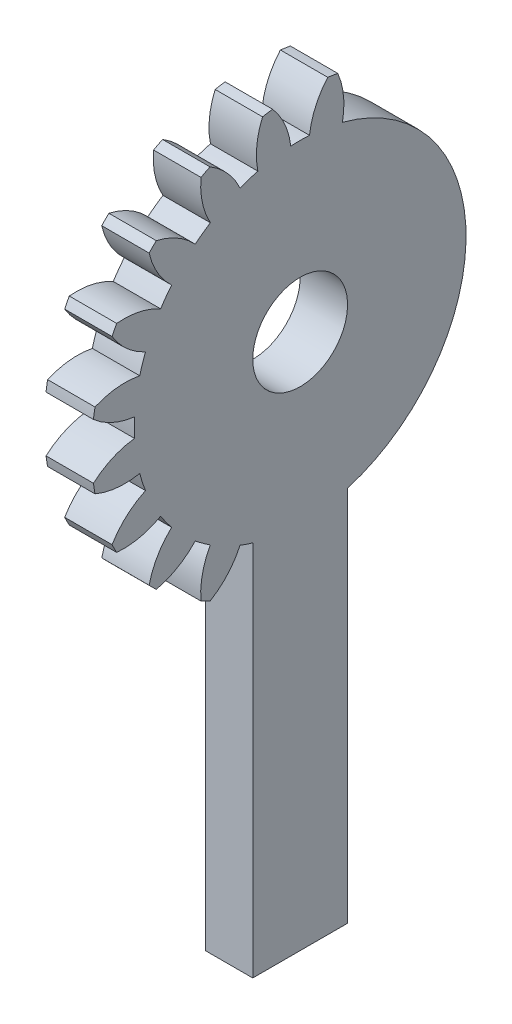
SolidWorks part; units mm, degrees
ref_plane "Plane1" through (0, 0, 0) normal (0, 0, 1) x (1, 0, 0)
ref_plane "Plane2" through (0, 0, 0) normal (0, 1, 0) x (1, 0, 0)
ref_plane "Plane3" through (0, 0, 0) normal (1, 0, 0) x (0, 0, -1)
other "Configuration Table"
sketch "HoldingSke" plane through (0, 0, 0) normal (0, 1, 0) x (1, 0, 0)
  line L0 (0, 0) -> (0.4698, -0.171)
  line L1 (-15, 0) -> (100, 0) construction
  line L2 (0, 0) -> (-2.1039, 2.3779)
  line L3 (0, 0) -> (-11.863, 4.5341)
  line L4 (0, 0) -> (8.1152, 2.9537)
  line L5 (0, 0) -> (-46.8476, -17.4728)
  line L6 (0, 0) -> (-4.1448, -2.7965)
  line L7 (-2.1039, 2.3779) -> (8.6586, 51.2059)
  line L8 (-76.2, 54.61) -> (-75.5, 54.61)
  line L9 (-71.009, 38.7566) -> (-53.1078, 45.2721)
  line L10 (-76.2, 71.12) -> (104.1128, 71.12)
  line L11 (0, 0) -> (-5, 0)
  line L12 (-76.2, 101.6) -> (-76.133, 101.6)
  line L13 (24.9733, 27.94) -> (52.9518, 28.4284)
  line L14 (24.9733, 27.94) -> (24.9743, 27.94)
  line L15 (24.9733, 27.94) -> (100.4006, 29.5858)
  line L16 (-63.627, -2) -> (-12.827, -2)
  circle A0 centre (0, 0) radius 2
  circle A1 centre (0, 0) radius 17.499
  circle A2 centre (0, 0) radius 37.5
  circle A3 centre (0, 0) radius 2
  dimension "MHD" = 34.998
  dimension "Hub_dia" = 75
  dimension "Bore" = 4
  dimension "MBD" = 4
  dimension "Num_teeth" = 20
  dimension "Pitch" = 0.5
  dimension "Overall_len" = 50
  dimension "Show_teeth" = 20
  dimension "Thickness" = 5
  dimension "OAL" = 50.0001
  dimension "T_dim" = 0.7
  dimension "Ap" = 20
  dimension "H" = 19.05
  dimension "Pitch_radius" = 180.3128
  dimension "Width" = 5
  dimension "Backlash" = 0.067
  dimension "Addendum_fac" = 1
  dimension "Dedendum_fac" = 1.25
  dimension "Clearance_fac" = 0.25
  dimension "Dedendum_add" = 0.001
  dimension "Module" = 2
sketch "BasProSke" plane through (0, 0, 0) normal (0, 1, 0) x (1, 0, 0)
  line L0 (-10, 0) -> (60, 0) construction
  line L1 (0, 0) -> (0, 22)
  line L2 (0, 0) -> (5, 0)
  line L3 (5, 0) -> (5, 22)
  line L4 (5, 22) -> (0, 22)
  dimension "Thickness" = 5
  dimension "Diameter" = 44
revolve "Base-Revolve" add sketch "BasProSke" angle 360 about L0
sketch "TooCutSke" plane through (0, 0, 0) normal (1, 0, 0) x (0, 0, -1)
  line L1 (0, 0) -> (0, 107) construction
  line L2 (0, 0) -> (-1.6864, 19.9288) construction
  line L3 (0, 0) -> (-6.2409, 39.4033) construction
  line L4 (-1.6864, 19.9288) -> (-3.1204, 19.7016) construction
  arc A0 (0.9862, 17.4712) -> (-0.9862, 17.4712) centre (0, 0) ccw
  arc A1 (2.9329, 21.8293) -> (-2.9329, 21.8293) centre (0, 0) ccw
  circle A2 centre (0, 0) radius 20 construction
  circle A3 centre (0, 0) radius 18.7939 construction
  arc A4 (-0.9862, 17.4712) -> (-2.9329, 21.8293) centre (-8.9313, 16.536) ccw
  arc A5 (2.9329, 21.8293) -> (0.9862, 17.4712) centre (8.9313, 16.536) ccw
  dimension "Root_dia" = 34.998
  dimension "Overcut_dia" = 44.0508
  dimension "Pitch_dia" = 40
  dimension "Base_dia" = 37.5877
  dimension "Flank_rad" = 8
  dimension "Half_ang" = 9
  dimension "Half_CT" = 1.4519
extrude "ToothCut" cut sketch "TooCutSke" along normal through all
fillet "Breaks" [suppressed] radius 0.04
fillet "RootFillets" [suppressed] radius 0.501
pattern_circular "TeethCuts" count 20 every 18 about axis through (-10, 0, 0) along (1, 0, 0) of "ToothCut", "RootFillets", "Breaks"
sketch "HubNeaOneSke" plane through (0, 0, 0) normal (-1, 0, 0) x (0, 0, 1)
  circle A0 centre (0, 0) radius 17.499
  dimension "Diameter" = 34.998
extrude "HubNearOne" [suppressed] add sketch "HubNeaOneSke" along normal blind 45.0001
sketch "HubNeaBotSke" plane through (0, 0, 0) normal (-1, 0, 0) x (0, 0, 1)
  circle A0 centre (0, 0) radius 17.499
  dimension "Diameter" = 34.998
extrude "HubNearBoth" [suppressed] add sketch "HubNeaBotSke" along normal blind 22.5
ref_plane "FarPln" through (5, 0, 0) normal (1, 0, 0) x (0, 0, -1)
sketch "HubFarSke" plane through (5, 0, 0) normal (1, 0, 0) x (0, 0, -1)
  circle A0 centre (0, 0) radius 17.499
  dimension "Diameter" = 34.998
extrude "HubFar" [suppressed] add sketch "HubFarSke" along normal blind 22.5
sketch "BorSke" plane through (0, 0, 0) normal (1, 0, 0) x (0, 0, -1)
  circle A0 centre (0, 0) radius 2
  dimension "Diameter" = 4
extrude "Bore" cut sketch "BorSke" along normal mid plane 100.0001
sketch "KeySke" plane through (0, 0, 0) normal (1, 0, 0) x (0, 0, -1)
  line L0 (-0.8, 0) -> (-0.8, 2.7)
  line L1 (-0.8, 2.7) -> (0.8, 2.7)
  line L2 (0.8, 2.7) -> (0.8, 0)
  line L3 (0, 0) -> (0, 34) construction
  line L4 (-0.8, 0) -> (0.8, 0)
  dimension "Offset" = 2.7
  dimension "Width" = 1.6
extrude "Keyway" [suppressed] cut sketch "KeySke" along normal mid plane 100.0001
pattern_circular "Keyway2" [suppressed] count 2 every 90 about axis through (-10, 0, 0) along (1, 0, 0)
sketch "Sketch1" plane through (0, 0, 0) normal (-1, 0, 0) x (0, 0, 1)
  line L0 (0, 0) -> (0, -16.5125)
  line L1 (5, -16.5125) -> (-5, -16.5125)
  line L2 (5, -16.5125) -> (5, -56.5125)
  line L3 (5, -56.5125) -> (-5, -56.5125)
  line L4 (-5, -16.5125) -> (-5, -56.5125)
  point P9 (0, -16.5125)
  dimension "D1" = 10
  dimension "D2" = 40
extrude "Boss-Extrude1" add sketch "Sketch1" against normal up to surface (5 mm away) contours L1 L4 L3 L2 up to face at (5, 0, 2)
sketch "Sketch2" plane through (0, 0, 0) normal (-1, 0, 0) x (0, 0, 1)
  line L0 (-5, -16.7695) -> (-4.461, 16.9208)
  line L1 (-4.461, 16.9208) -> (-7.7926, 24.2857)
  line L2 (-7.7926, 24.2857) -> (-28.6342, 9.7831)
  line L3 (-28.6342, 9.7831) -> (-18.2134, -22.1035)
  line L4 (-18.2134, -22.1035) -> (-10.9621, -23.4481)
  line L5 (-10.9621, -23.4481) -> (-5, -16.7695)
extrude "Cut-Extrude1" cut sketch "Sketch2" against normal through all
sketch "Sketch4" plane through (0, 0, 0) normal (-1, 0, 0) x (0, 0, 1)
  circle A0 centre (0, 0) radius 17.499
extrude "Boss-Extrude2" add sketch "Sketch4" against normal up to surface (5 mm away) up to face at (5, 0.2166, 10.9195)
sketch "Sketch5" plane through (0, 0, 0) normal (-1, 0, 0) x (0, 0, 1)
  circle A0 centre (0, 0) radius 5
  dimension "D1" = 10
extrude "Cut-Extrude2" cut sketch "Sketch5" against normal up to surface (5 mm away) up to face at (5, 0.2213, 10.6294)
equation "' \"Module@HoldingSke\" = 6.35"
equation "' \"Num_teeth@HoldingSke\" = 12"
equation "' \"Ap@HoldingSke\" =  20"
equation "' \"Ap@HoldingSke\" = 20"
equation "' \"Width@HoldingSke\" = 0.5 * 25.4"
equation "' \"Hub_dia@HoldingSke\"= 1 * 25.4"
equation "' \"Hub_dia@HoldingSke\" = 1 * 25.4"
equation "' \"Overall_len@HoldingSke\" = 1.0 * 25.4"
equation "' \"Bore@HoldingSke\" = 0.75 * 25.4"
equation "' \"T_dim@HoldingSke\" = 0.1 * 25.4"
equation "' \"Width@KeySke\" = 0.25 * 25.4"
equation "' \"Show_teeth@HoldingSke\" = 13"
equation "' \"Backlash@HoldingSke\" = 0.009 * 25.4"
equation "' \"Addendum_fac@HoldingSke\" = 1.0"
equation "' \"Dedendum_fac@HoldingSke\" = 1.25"
equation "' \"Dedendum_add@HoldingSke\" = 0.00005 * 25.4"
equation "' \"Clearance_fac@HoldingSke\" = 0.25"
equation "\"Pitch@HoldingSke\" = 1 / \"Module@HoldingSke\""
equation "\"Overcut_dia@TooCutSke\" = (\"Num_teeth@HoldingSke\" + 2 * \"Addendum_fac@HoldingSke\") / \"Pitch@HoldingSke\" + 0.002 * 25.4"
equation "\"Pitch_dia@TooCutSke\" = \"Num_teeth@HoldingSke\" / \"Pitch@HoldingSke\""
equation "\"Base_dia@TooCutSke\" = \"Num_teeth@HoldingSke\" / \"Pitch@HoldingSke\" * cos((\"Ap@HoldingSke\"  * 3.14159265 / 180))"
equation "\"Root_dia@TooCutSke\" = (\"Num_teeth@HoldingSke\" + 2) / \"Pitch@HoldingSke\" - 2 * (\"Addendum_fac@HoldingSke\" + \"Dedendum_fac@HoldingSke\") / \"Pitch@HoldingSke\" - \"Dedendum_add@HoldingSke\" * 2"
equation "\"Half_ang@TooCutSke\" = 180 / \"Num_teeth@HoldingSke\""
equation "\"Half_CT@TooCutSke\" = \"Num_teeth@HoldingSke\" / \"Pitch@HoldingSke\" * sin((3.14159265 / 2 / \"Num_teeth@HoldingSke\")) / 2 - 7 * \"Backlash@HoldingSke\" / 4"
equation "\"Flank_rad@TooCutSke\" = \"Num_teeth@HoldingSke\" / \"Pitch@HoldingSke\" / 5"
equation "\"Radius@RootFillets\" = \"Clearance_fac@HoldingSke\" / \"Pitch@HoldingSke\" + \"Dedendum_add@HoldingSke\""
equation "\"Break_rad@Breaks\" = 0.02 / \"Pitch@HoldingSke\""
equation "\"Thickness@HoldingSke\" = \"Width@HoldingSke\""
equation "\"OAL@HoldingSke\" = \"Thickness@HoldingSke\""
equation "\"MHD@HoldingSke\" = (\"Num_teeth@HoldingSke\" + 2) / \"Pitch@HoldingSke\" - 2 * (\"Addendum_fac@HoldingSke\" + \"Dedendum_fac@HoldingSke\")  / \"Pitch@HoldingSke\" - \"Dedendum_add@HoldingSke\" * 2"
equation "\"MBD@HoldingSke\" = (\"Num_teeth@HoldingSke\" + 2) / \"Pitch@HoldingSke\" - 2 * (\"Addendum_fac@HoldingSke\" + \"Dedendum_fac@HoldingSke\")  / \"Pitch@HoldingSke\" - \"Dedendum_add@HoldingSke\" * 2 - 0.002 * 25.4"
equation "\"MHD@HoldingSke\" = ((sgn( \"MHD@HoldingSke\" - \"Hub_dia@HoldingSke\" )-1)*( \"MHD@HoldingSke\" - \"Hub_dia@HoldingSke\" ))/-2+ \"Hub_dia@HoldingSke\""
equation "\"MBD@HoldingSke\" = ((sgn( \"MBD@HoldingSke\" - \"Bore@HoldingSke\" )-1)*( \"MBD@HoldingSke\" - \"Bore@HoldingSke\" ))/-2+ \"Bore@HoldingSke\""
equation "\"OAL@HoldingSke\" = ((sgn( \"OAL@HoldingSke\" - \"Overall_len@HoldingSke\" )+1)*( \"OAL@HoldingSke\" - \"Overall_len@HoldingSke\" ))/2 + \"Overall_len@HoldingSke\" + 0.000002 * 25.4"
equation "\"Num_teeth@TeethCuts\" = int( \"Show_teeth@HoldingSke\" ) + 1"
equation "\"Num_teeth@TeethCuts\" = ((sgn( \"Num_teeth@TeethCuts\" - \"Num_teeth@HoldingSke\" )-1)*( \"Num_teeth@TeethCuts\" - \"Num_teeth@HoldingSke\" ))/-2+ \"Num_teeth@HoldingSke\""
equation "\"Num_teeth@TeethCuts\" = ((sgn( \"Num_teeth@TeethCuts\" - 2.0)+1)*( \"Num_teeth@TeethCuts\" - 2.0))/2 +2.0"
equation "\"Angle@TeethCuts\" = 360.0 / \"Num_teeth@HoldingSke\""
equation "\"Diameter@BasProSke\" = (\"Num_teeth@HoldingSke\" + 2 * \"Addendum_fac@HoldingSke\") / \"Pitch@HoldingSke\""
equation "\"Thickness@BasProSke\"  = \"Thickness@HoldingSke\""
equation "' \"Fillet_rad@BasProSke\" =  \"Thickness@HoldingSke\" * 0.05"
equation "' \"Fillet_rad@BasProSke\" = \"Thickness@HoldingSke\" * 0.05"
equation "\"MHD@HoldingSke\" = ((sgn( \"MHD@HoldingSke\" - \"Root_dia@TooCutSke\" )-1)*( \"MHD@HoldingSke\" - \"Root_dia@TooCutSke\" ))/-2+ \"Root_dia@TooCutSke\""
equation "\"Diameter@HubNeaOneSke\" = \"MHD@HoldingSke\""
equation "\"Length@HubNearOne\" = \"OAL@HoldingSke\" - \"Thickness@BasProSke\""
equation "\"Diameter@HubNeaBotSke\" = \"MHD@HoldingSke\""
equation "\"Length@HubNearBoth\" = ( \"OAL@HoldingSke\" - \"Thickness@BasProSke\" ) / 2.0"
equation "\"Thickness@FarPln\" = \"Thickness@BasProSke\""
equation "\"Diameter@HubFarSke\" = \"MHD@HoldingSke\""
equation "\"Length@HubFar\" = ( \"OAL@HoldingSke\" - \"Thickness@BasProSke\" ) / 2.0"
equation "\"Diameter@BorSke\" = \"MBD@HoldingSke\""
equation "\"D1@Bore\" = \"OAL@HoldingSke\" * 2.0"
equation "\"D1@Keyway\" = \"OAL@HoldingSke\" * 2.0"
equation "\"Offset@KeySke\" = \"T_dim@HoldingSke\" + \"MBD@HoldingSke\" / 2.0"
